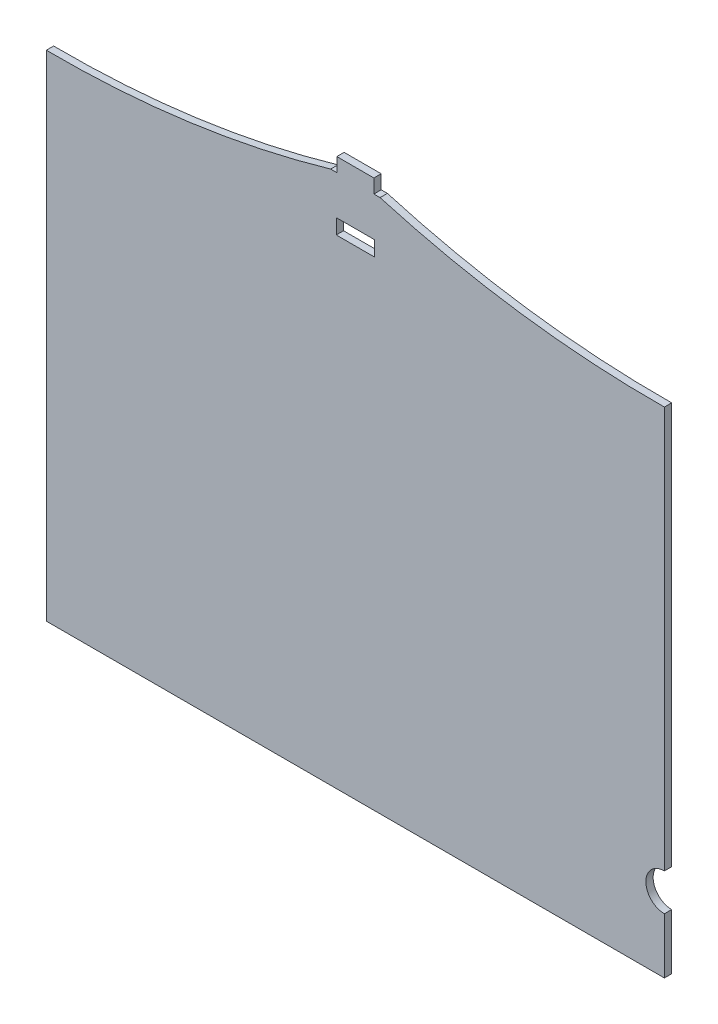
SolidWorks part; units mm, degrees
ref_plane "Front Plane" through (0, 0, 0) normal (0, 0, 1) x (1, 0, 0)
ref_plane "Top Plane" through (0, 0, 0) normal (0, 1, 0) x (1, 0, 0)
ref_plane "Right Plane" through (0, 0, 0) normal (1, 0, 0) x (0, 0, -1)
sketch "Sketch1" plane through (0, 0, 0) normal (0, 0, 1) x (1, 0, 0)
  line L0 (0.1712, 69.4697) -> (2.6712, 69.4697)
  line L2 (-114.8288, 53.5997) -> (-114.8288, -146.4003)
  line L3 (-114.8288, -146.4003) -> (135.1712, -146.4003)
  line L4 (135.1712, 53.5997) -> (135.1712, -108.9003)
  line L5 (17.6712, 69.4697) -> (20.1712, 69.4697)
  line L7 (2.6712, 69.4697) -> (2.6712, 75.0997)
  line L8 (2.6712, 75.0997) -> (17.6712, 75.0997)
  line L9 (17.6712, 69.4697) -> (17.6712, 75.0997)
  line L10 (135.1712, -123.9003) -> (135.1712, -146.4003)
  line L11 (2.4462, 53.5997) -> (17.8962, 53.5997)
  line L12 (2.4462, 53.5997) -> (2.4462, 47.5197)
  line L13 (2.4462, 47.5197) -> (17.8962, 47.5197)
  line L14 (17.8962, 53.5997) -> (17.8962, 47.5197)
  arc A0 (-114.8288, 53.5997) -> (0.1712, 69.4697) centre (-111.4318, 453.5852) ccw
  arc A1 (20.1712, 69.4697) -> (135.1712, 53.5997) centre (131.7741, 453.5852) ccw
  arc A2 (135.1712, -108.9003) -> (135.1712, -123.9003) centre (135.1712, -116.4003) ccw
  point P17 (10.1712, 75.0997)
  point P18 (10.1712, 53.5997)
  dimension "D11" = 400
  dimension "D12" = 400
  dimension "D13" = 15
  dimension "D1" = 200
  dimension "D2" = 250
  dimension "D4" = 20
  dimension "D3" = 15.87
  dimension "D5" = 5.63
  dimension "D6" = 15
  dimension "D7" = 15.45
  dimension "D8" = 6.08
  dimension "D9" = 125
  dimension "D10" = 10
  dimension "D14" = 30
extrude "Boss-Extrude1" add sketch "Sketch1" along normal blind 2.95
equation "\"Width\"= 250"
equation "\"Height\"= 200"
equation "\"thin Acrylic\"= 2.95"
equation "\"D1@Sketch1\"=\"Height\""
equation "\"D2@Sketch1\"=\"Width\""
equation "\"D1@Boss-Extrude1\"=\"thin Acrylic\""
equation "\"Thick acrylic\"= 5.63"
equation "\"Drone height\"= 21.5"
equation "\"Guard height\"= \"Drone height\" - \"Thick acrylic\""
equation "\"Support width\"= 20"
equation "\"D4@Sketch1\"=\"Support width\""
equation "\"D3@Sketch1\"=\"Guard height\""
equation "\"attach width\"= 15"
equation "\"D5@Sketch1\"=\"Thick acrylic\""
equation "\"D6@Sketch1\"=\"attach width\""
equation "\"gap\" = 0.45"
equation "\"D7@Sketch1\"=\"attach width\"+\"gap\""
equation "\"D8@Sketch1\"=\"Thick acrylic\"+\"gap\""
equation "\"D9@Sketch1\"=\"Width\"/2"
equation "\"D10@Sketch1\"=\"Support width\"/2"
equation "\"wire hole\"= 15"
equation "\"D13@Sketch1\"=\"wire hole\""
